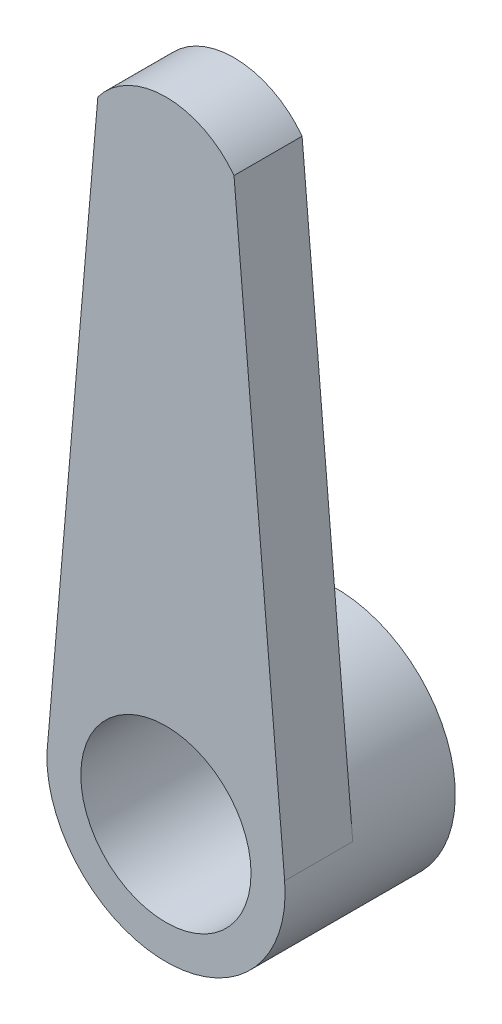
SolidWorks part; units mm, degrees
ref_plane "Front Plane" through (0, 0, 0) normal (0, 0, 1) x (1, 0, 0)
ref_plane "Top Plane" through (0, 0, 0) normal (0, 1, 0) x (1, 0, 0)
ref_plane "Right Plane" through (0, 0, 0) normal (1, 0, 0) x (0, 0, -1)
ref_plane "Plane1" through (0, 0, -2) normal (0, 0, -1) x (-1, 0, 0)
sketch "Sketch1" plane through (0, 0, -2) normal (0, 0, -1) x (-1, 0, 0)
  line L0 (-2, 17.5) -> (-3.487, 0.3015)
  line L1 (3.5, 0) -> (2, 17.5)
  arc A0 (-3.487, 0.3015) -> (3.5, 0) centre (0, 0) ccw
  arc A1 (2, 17.5) -> (-2, 17.5) centre (0, 16) ccw
extrude "Boss-Extrude1" add sketch "Sketch1" against normal blind 2
sketch "Sketch2" plane through (0, 0, -2) normal (0, 0, -1) x (-1, 0, 0)
  line L0 (3.4489, 0.5956) -> (3.5, 0)
  arc A0 (3.5, 0) -> (3.4489, 0.5956) centre (0, 0) cw
extrude "Boss-Extrude2" add sketch "Sketch2" along normal blind 3
hole_wizard "Ø5.0 (5) Diameter Hole1" positions "Sketch4" profile "Sketch3" hole size "Ø5.0" standard "ANSI Metric"
sketch "Sketch4" plane through (0, 0, -5) normal (0, 0, -1) x (-1, 0, 0)
  point P0 (0, 0)
sketch "Sketch3" plane through (0, 0, -5) normal (1, 0, 0) x (0, 1, 0)
  line L0 (0, 0) -> (0, 5)
  line L1 (0, 5) -> (2.5, 5)
  line L2 (2.5, 5) -> (2.5, 0)
  line L5 (2.5, 0) -> (0, 0)
  line L11 (0, -6.35) -> (0, 107.95) construction
  dimension "Thru Hole Dia." = 5
  dimension "Thru Hole Depth" = 5
